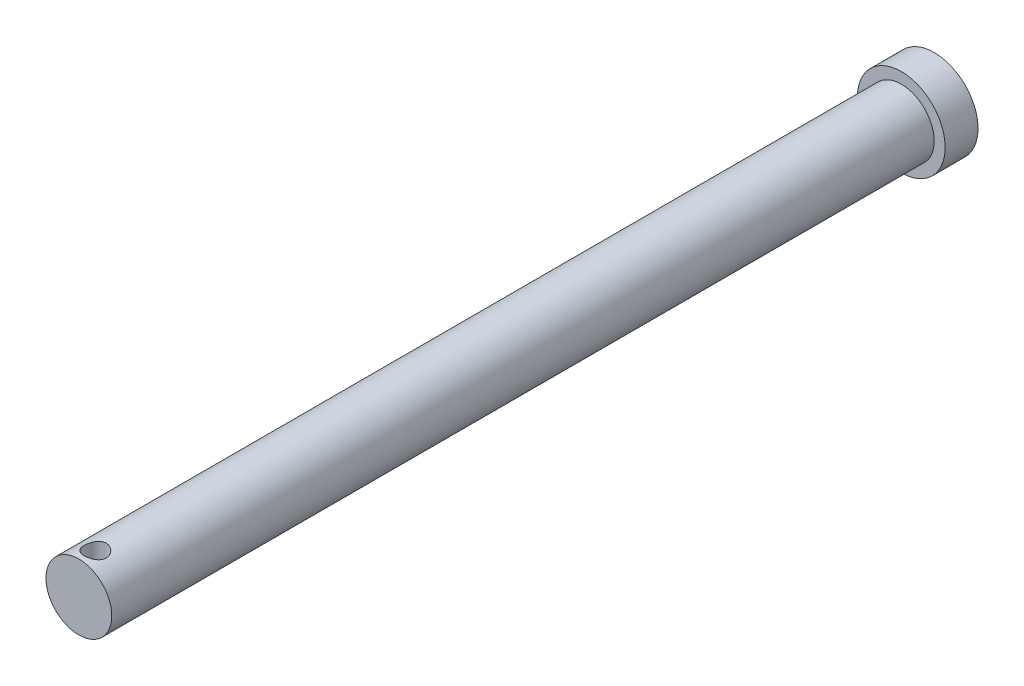
SolidWorks part; units mm, degrees
ref_plane "Front Plane" through (0, 0, 0) normal (0, 0, 1) x (1, 0, 0)
ref_plane "Top Plane" through (0, 0, 0) normal (0, 1, 0) x (1, 0, 0)
ref_plane "Right Plane" through (0, 0, 0) normal (1, 0, 0) x (0, 0, -1)
sketch "Sketch1" plane through (0, 0, 0) normal (0, 0, 1) x (1, 0, 0)
  circle A0 centre (0, 0) radius 3
  dimension "D1" = 6
extrude "Boss-Extrude1" add sketch "Sketch1" along normal mid plane 75
sketch "Sketch2" plane through (0, 0, -37.5) normal (0, 0, -1) x (-1, 0, 0)
  circle A0 centre (0, 0) radius 4
  dimension "D1" = 8
extrude "Boss-Extrude2" add sketch "Sketch2" along normal blind 3
sketch "Sketch3" plane through (0, 0, 0) normal (0, 1, 0) x (1, 0, 0)
  line L1 (3, -37.5) -> (3, 37.5) construction
  line L2 (-3, -37.5) -> (3, -37.5) construction
  circle A0 centre (0, -36) radius 1
  dimension "D3" = 2
  dimension "D1" = 3
  dimension "D2" = 1.5
extrude "Cut-Extrude1" cut sketch "Sketch3" against normal through all both and the other way through all
